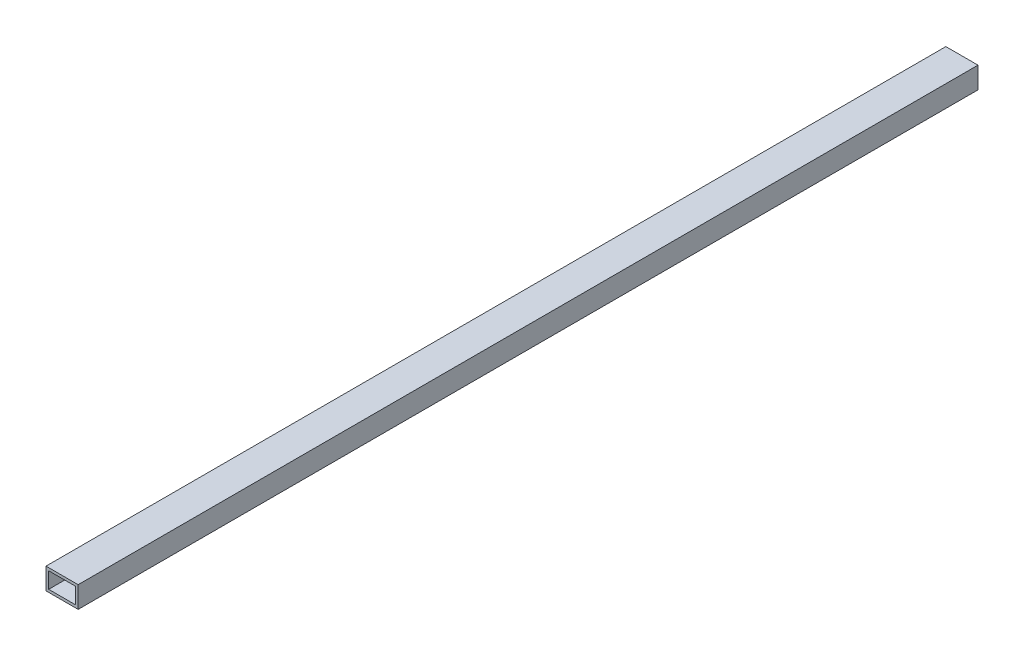
SolidWorks part; units mm, degrees
ref_plane "Front Plane" through (0, 0, 0) normal (0, 0, 1) x (1, 0, 0)
ref_plane "Top Plane" through (0, 0, 0) normal (0, 1, 0) x (1, 0, 0)
ref_plane "Right Plane" through (0, 0, 0) normal (1, 0, 0) x (0, 0, -1)
sketch "Sketch1" plane through (0, 0, 0) normal (0, 0, 1) x (1, 0, 0)
  line L1 (-19.05, 12.7) -> (19.05, 12.7)
  line L2 (-19.05, 12.7) -> (-19.05, -12.7)
  line L3 (-19.05, -12.7) -> (19.05, -12.7)
  line L4 (19.05, 12.7) -> (19.05, -12.7)
  line L5 (-19.05, 12.7) -> (19.05, -12.7) construction
  line L6 (-19.05, -12.7) -> (19.05, 12.7) construction
  point P0 (0, 0)
  dimension "D1" = 38.1
  dimension "D2" = 25.4
extrude "Boss-Extrude1" add sketch "Sketch1" along normal blind 1066.8
shell "Shell1" thickness 3.175
